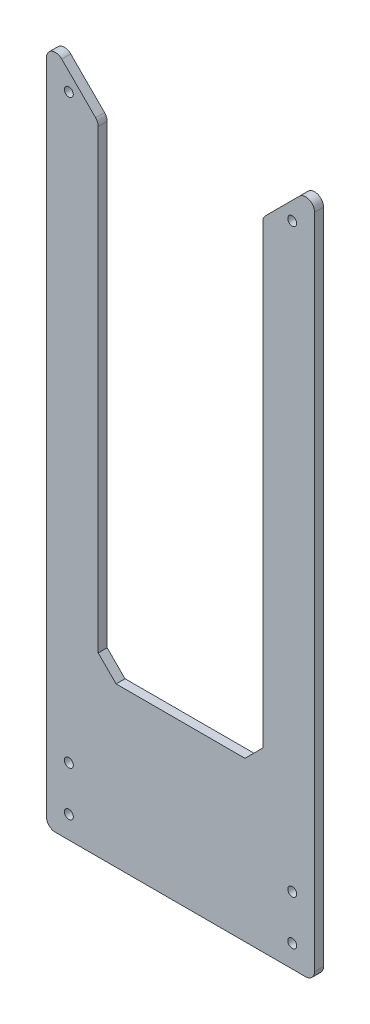
SolidWorks part; units mm, degrees
ref_plane "Front Plane" through (0, 0, 0) normal (0, 0, 1) x (1, 0, 0)
ref_plane "Top Plane" through (0, 0, 0) normal (0, 1, 0) x (1, 0, 0)
ref_plane "Right Plane" through (0, 0, 0) normal (1, 0, 0) x (0, 0, -1)
sketch "Model" plane through (0, 0, 0) normal (0, 0, 1) x (1, 0, 0)
  line L0 (82.6519, -1) -> (54.6519, -1)
  line L1 (53.6519, 0) -> (53.6519, 73.5858)
  line L2 (83.6519, 0) -> (83.6519, 73.5858)
  line L3 (55.359, 74.2929) -> (59.149, 70.5029)
  line L4 (59.4419, 69.7958) -> (59.4419, 18.78)
  line L5 (61.4418, 16.78) -> (75.8618, 16.78)
  line L6 (77.8619, 18.78) -> (77.8619, 69.7958)
  line L7 (78.1547, 70.5029) -> (81.9447, 74.2929)
  line L8 (59.4419, 18.78) -> (61.4418, 16.78)
  line L9 (75.8618, 16.78) -> (77.8619, 18.78)
  circle A0 centre (56.1519, 6.5) radius 0.5
  circle A1 centre (56.1519, 71.5) radius 0.5
  circle A2 centre (81.1519, 6.5) radius 0.5
  circle A3 centre (81.1519, 71.5) radius 0.5
  circle A4 centre (56.1519, 1.5) radius 0.5
  circle A5 centre (81.1519, 1.5) radius 0.5
  arc A6 (82.6519, -1) -> (83.6519, 0) centre (82.6519, 0) ccw
  arc A7 (53.6519, 0) -> (54.6519, -1) centre (54.6519, 0) ccw
  arc A8 (83.6519, 73.5858) -> (81.9447, 74.2929) centre (82.6519, 73.5858) ccw
  arc A9 (55.359, 74.2929) -> (53.6519, 73.5858) centre (54.6519, 73.5858) ccw
  arc A10 (59.4419, 69.7958) -> (59.149, 70.5029) centre (58.4419, 69.7958) ccw
  arc A11 (78.1547, 70.5029) -> (77.8619, 69.7958) centre (78.8619, 69.7958) ccw
extrude "Boss-Extrude1" add sketch "Model" along normal blind 1
